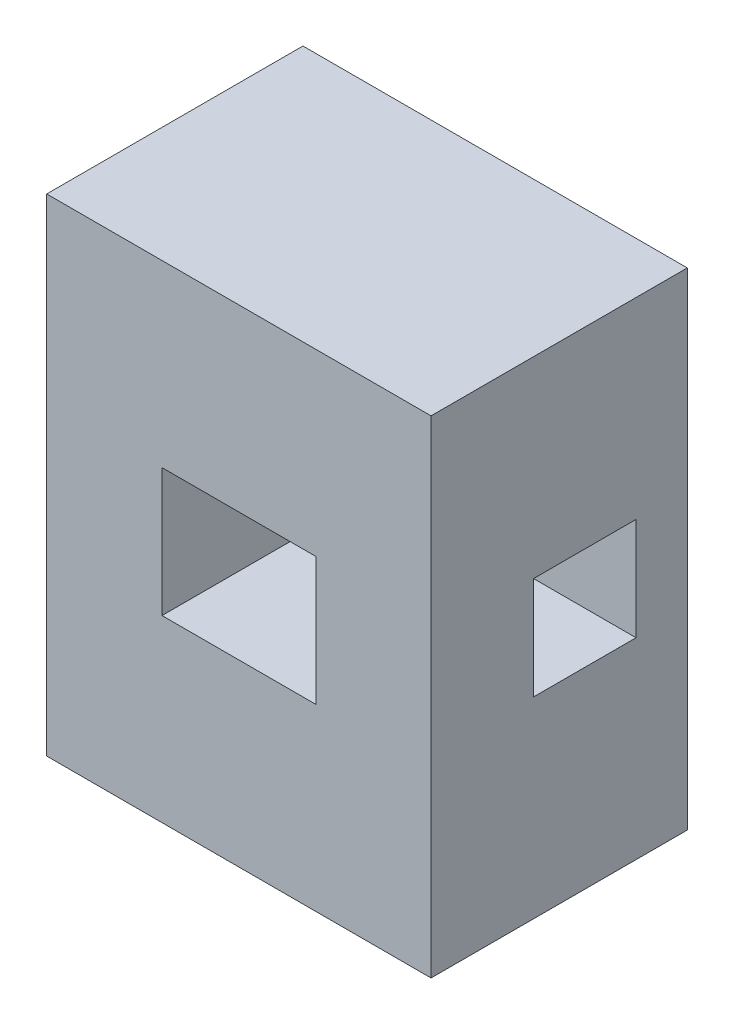
SolidWorks part; units mm, degrees
ref_plane "Front Plane" through (0, 0, 0) normal (0, 0, 1) x (1, 0, 0)
ref_plane "Top Plane" through (0, 0, 0) normal (0, 1, 0) x (1, 0, 0)
ref_plane "Right Plane" through (0, 0, 0) normal (1, 0, 0) x (0, 0, -1)
sketch "Sketch1" plane through (0, 0, 0) normal (0, 1, 0) x (1, 0, 0)
  line L1 (0, 0) -> (30, 0)
  line L2 (0, 0) -> (0, 20)
  line L3 (0, 20) -> (30, 20)
  line L4 (30, 0) -> (30, 20)
  dimension "D1" = 30
  dimension "D2" = 20
extrude "Boss-Extrude1" add sketch "Sketch1" along normal blind 38
sketch "Sketch2" plane through (0, 0, 0) normal (0, 0, 1) x (1, 0, 0)
  line L0 (0, 0) -> (30, 0) construction
  line L1 (30, 38) -> (30, 0) construction
  line L3 (9, 14) -> (21, 14)
  line L4 (9, 14) -> (9, 24)
  line L5 (9, 24) -> (21, 24)
  line L6 (21, 14) -> (21, 24)
  line L7 (9, 14) -> (21, 24) construction
  line L8 (9, 24) -> (21, 14) construction
  point P0 (15, 0)
  point P1 (30, 19)
  point P4 (15, 19)
  point P7 (15, 19)
  dimension "D1" = 10
  dimension "D2" = 12
  dimension "D3" = 0
  dimension "D4" = 0
extrude "Cut-Extrude1" cut sketch "Sketch2" against normal blind 38
sketch "Sketch3" plane through (30, 0, 0) normal (1, 0, 0) x (0, 0, -1)
  line L0 (0, 0) -> (20, 0) construction
  line L1 (20, 38) -> (20, 0) construction
  line L3 (8, 15) -> (16, 15)
  line L4 (8, 15) -> (8, 23)
  line L5 (8, 23) -> (16, 23)
  line L6 (16, 15) -> (16, 23)
  line L7 (8, 15) -> (16, 23) construction
  line L8 (8, 23) -> (16, 15) construction
  point P0 (10, 0)
  point P1 (20, 19)
  point P4 (12, 19)
  point P7 (12, 19)
  dimension "D1" = 8
  dimension "D2" = 8
  dimension "D3" = 0
  dimension "D4" = 2
extrude "Cut-Extrude2" cut sketch "Sketch3" against normal up to surface (9 mm away) up to face at (21, 19, -10)
sketch "Sketch4" plane through (21, 0, 0) normal (-1, 0, 0) x (0, 0, 1)
  line L1 (-20, 24) -> (-18, 24)
  line L2 (-20, 24) -> (-20, 14)
  line L3 (-20, 14) -> (-18, 14)
  line L4 (-18, 24) -> (-18, 14)
  dimension "D1" = 2
  dimension "D2" = 10
extrude "Boss-Extrude2" add sketch "Sketch4" along normal up to surface (12 mm away) up to face at (9, 19, -10)
